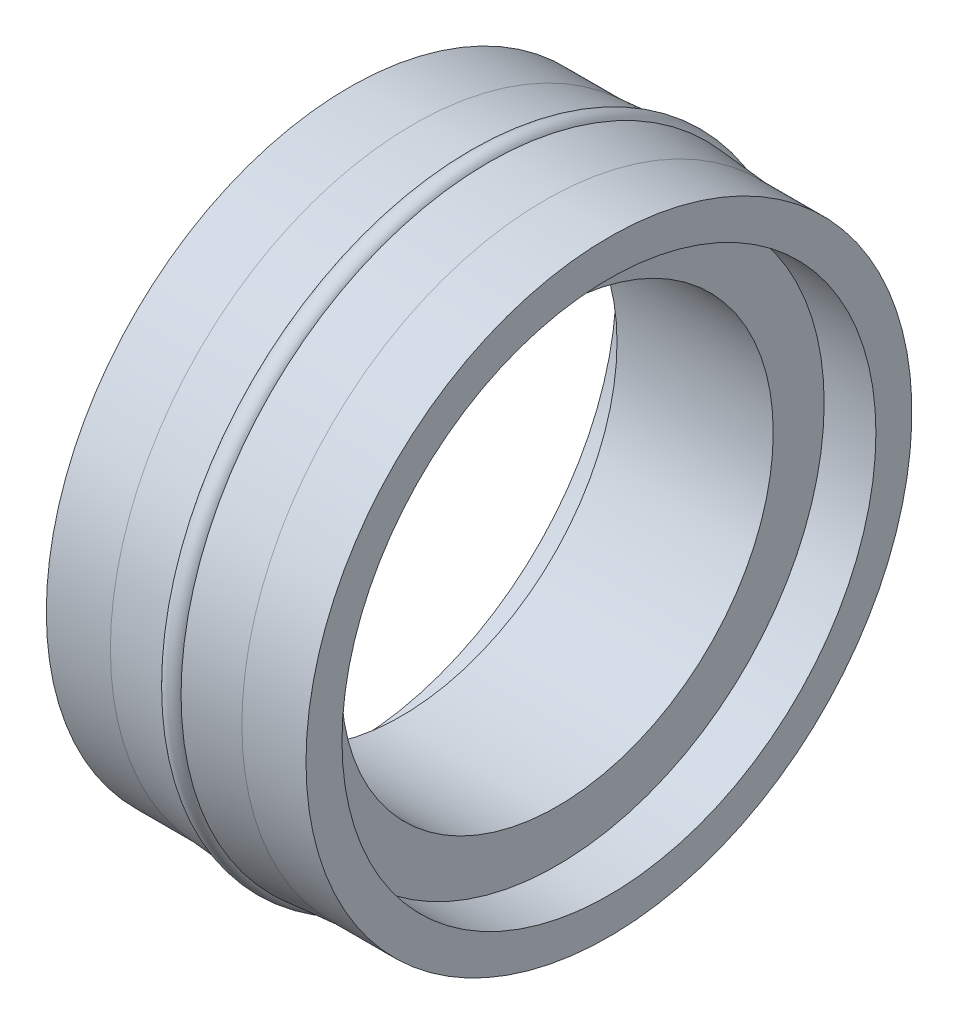
SolidWorks part; units mm, degrees
ref_plane "Front Plane" through (0, 0, 0) normal (0, 0, 1) x (1, 0, 0)
ref_plane "Top Plane" through (0, 0, 0) normal (0, 1, 0) x (1, 0, 0)
ref_plane "Right Plane" through (0, 0, 0) normal (1, 0, 0) x (0, 0, -1)
sketch "Sketch1" plane through (0, 0, 0) normal (0, 0, 1) x (1, 0, 0)
  line L0 (0, 0) -> (45, 0) construction
  line L3 (12, 24.5) -> (12, 21.5912)
  line L4 (12, 21.5912) -> (16.1829, 21.5912)
  line L5 (16.1829, 21.5912) -> (16.1829, 17.472)
  line L6 (16.1829, 17.472) -> (28.8171, 17.472)
  line L7 (28.8171, 17.472) -> (28.8171, 21.5912)
  line L8 (28.8171, 21.5912) -> (33.0019, 21.5912)
  line L9 (33.0019, 21.5912) -> (33.0019, 24.5)
  line L13 (33.0019, 24.5) -> (33, 24.5)
  line L14 (12, 24.5) -> (17.1829, 24.5)
  line L15 (22.5, 17.472) -> (22.5, 22.298) construction
  line L16 (20.2532, 24.7533) -> (21.7279, 24.875)
  line L17 (17.1829, 24.5) -> (20.2532, 24.7533)
  line L18 (33, 24.5) -> (27.8171, 24.5)
  line L20 (24.7468, 24.7533) -> (23.2721, 24.875)
  line L21 (27.8171, 24.5) -> (24.7468, 24.7533)
  arc A0 (21.7279, 24.875) -> (23.2721, 24.875) centre (22.5, 24.3849) cw
  point P22 (16.1829, 17.472)
  dimension "D1" = 45
revolve "Revolve1" add sketch "Sketch1" angle 360 about L0
